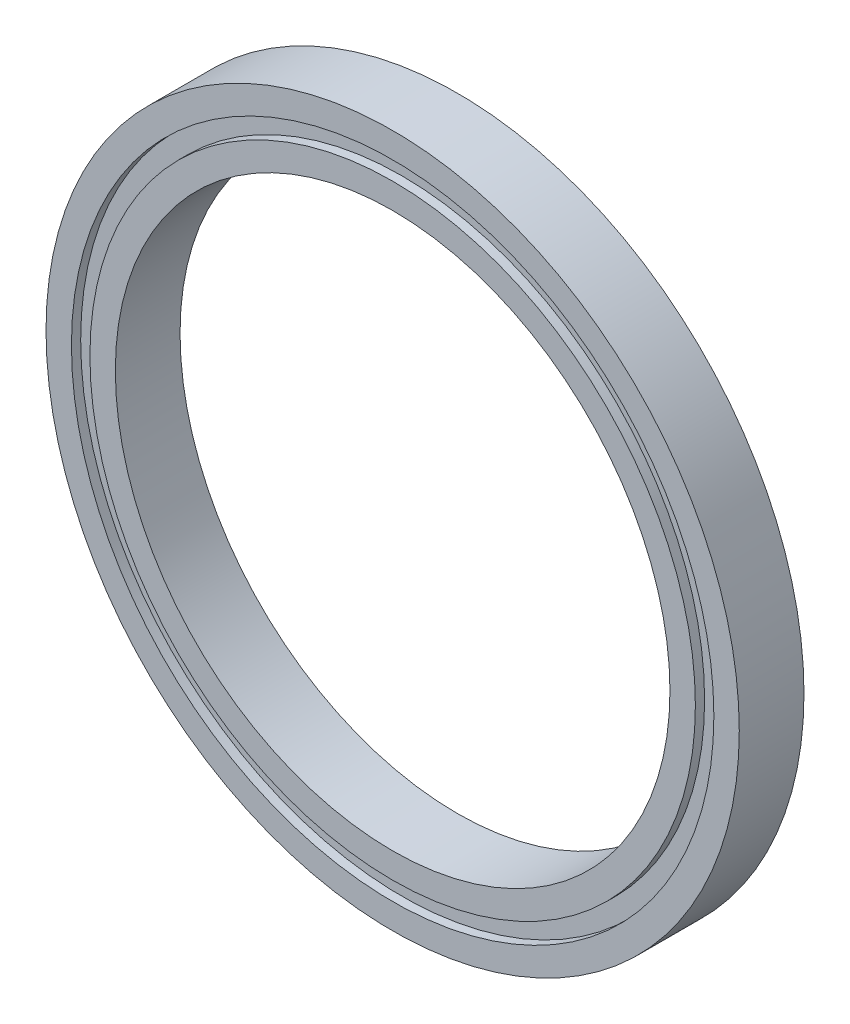
SolidWorks part; units mm, degrees
material "GCr15"
ref_plane "前视基准面" through (0, 0, 0) normal (0, 0, 1) x (1, 0, 0)
ref_plane "上视基准面" through (0, 0, 0) normal (0, 1, 0) x (1, 0, 0)
ref_plane "右视基准面" through (0, 0, 0) normal (1, 0, 0) x (0, 0, -1)
sketch "草图1" plane through (0, 0, 0) normal (1, 0, 0) x (0, 0, -1)
  line L0 (0, 40.0245) -> (0, 0) construction
  line L1 (0, 0) -> (-19.4628, 0) construction
  line L2 (7.9447, 33.75) -> (-15.3259, 33.75) construction
  line L3 (-3.5, 37.5) -> (3.5, 37.5)
  line L4 (3.5, 37.5) -> (3.5, 34.75)
  line L5 (3.5, 34.75) -> (2.5, 34.75)
  line L6 (2.5, 34.75) -> (2.5, 32.75)
  line L7 (3.5, 32.75) -> (2.5, 32.75)
  line L8 (3.5, 30) -> (3.5, 32.75)
  line L9 (-3.5, 30) -> (3.5, 30)
  line L10 (-3.5, 30) -> (-3.5, 32.75)
  line L11 (-3.5, 32.75) -> (-2.5, 32.75)
  line L12 (-2.5, 34.75) -> (-2.5, 32.75)
  line L13 (-3.5, 34.75) -> (-2.5, 34.75)
  line L14 (-3.5, 37.5) -> (-3.5, 34.75)
  point P12 (2.5, 33.75)
  point P15 (-2.5, 33.75)
  point P17 (0, 30)
  point P22 (0, 37.5)
  dimension "D1" = 60
  dimension "D2" = 75
  dimension "D3" = 7
  dimension "D4" = 2
  dimension "D5" = 5
revolve "旋转1" add sketch "草图1" angle 360 about L1
